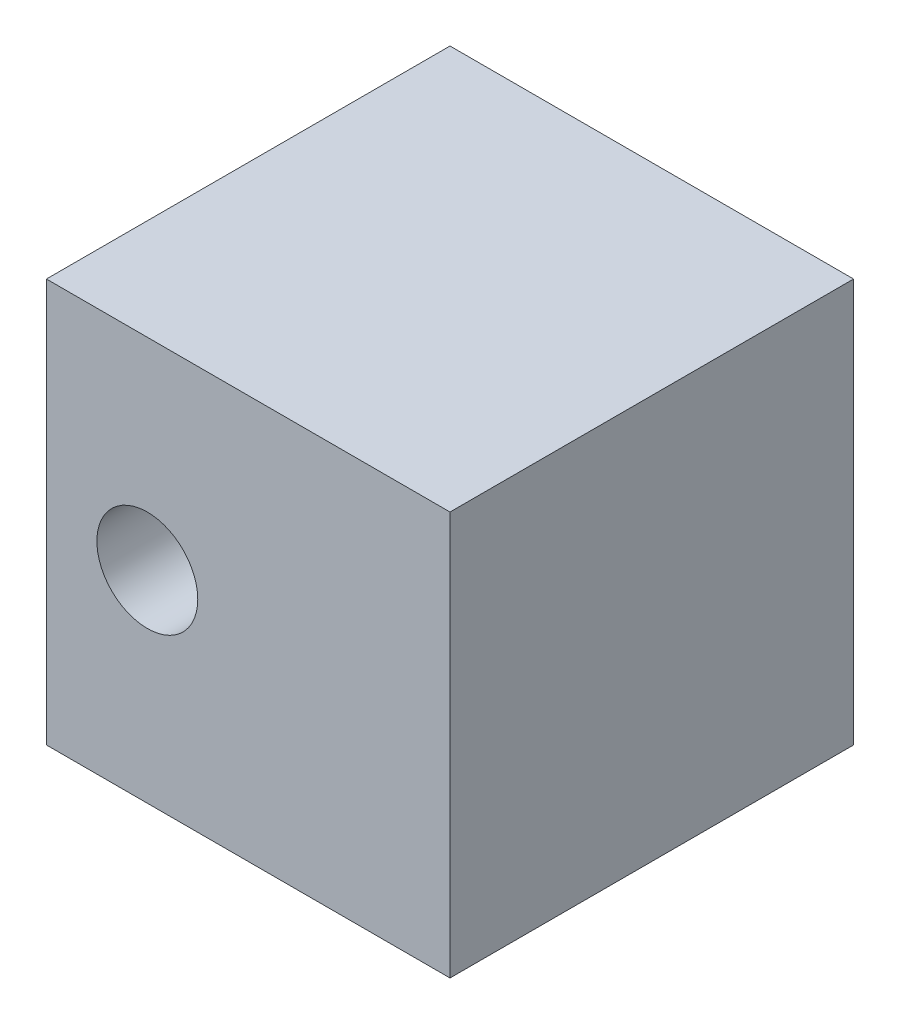
SolidWorks part; units mm, degrees
ref_plane "Front Plane" through (0, 0, 0) normal (0, 0, 1) x (1, 0, 0)
ref_plane "Top Plane" through (0, 0, 0) normal (0, 1, 0) x (1, 0, 0)
ref_plane "Right Plane" through (0, 0, 0) normal (1, 0, 0) x (0, 0, -1)
sketch "Sketch1" plane through (0, 0, 0) normal (0, 1, 0) x (1, 0, 0)
  line L1 (0, 0) -> (25.4, 0)
  line L2 (0, 0) -> (0, 25.4)
  line L3 (0, 25.4) -> (25.4, 25.4)
  line L4 (25.4, 0) -> (25.4, 25.4)
  dimension "D1" = 25.4
  dimension "D2" = 25.4
extrude "Boss-Extrude1" add sketch "Sketch1" along normal blind 25.4
sketch "Sketch2" plane through (0, 0, 0) normal (0, 0, 1) x (1, 0, 0)
  line L0 (0, 25.4) -> (25.4, 25.4) construction
  line L2 (0, 25.4) -> (0, 0) construction
  circle A0 centre (6.35, 12.7) radius 3.175
  point P4 (0, 0)
  point P5 (0, 0)
  point P6 (0, 23.0897)
  point P7 (0, 0)
  dimension "D1" = 6.35
  dimension "D2" = 12.7
  dimension "D3" = 6.35
extrude "Cut-Extrude1" cut sketch "Sketch2" against normal through all
